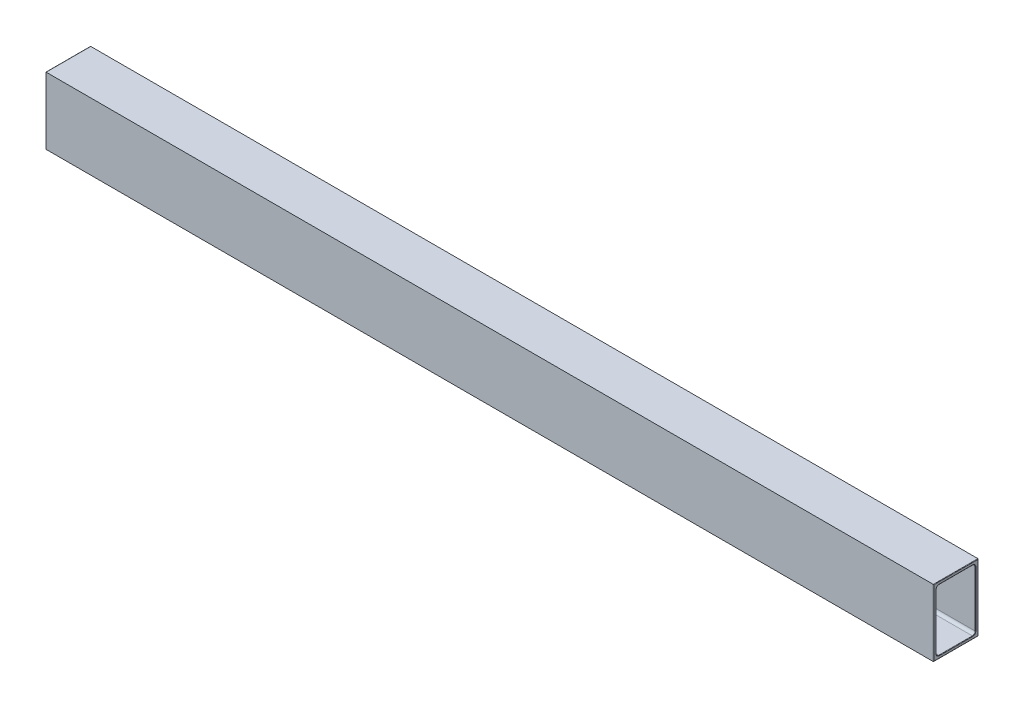
SolidWorks part; units mm, degrees
material "ASTM A500 Grade B Steel"
ref_plane "Front Plane" through (0, 0, 0) normal (0, 0, 1) x (1, 0, 0)
ref_plane "Top Plane" through (0, 0, 0) normal (0, 1, 0) x (1, 0, 0)
ref_plane "Right Plane" through (0, 0, 0) normal (1, 0, 0) x (0, 0, -1)
sketch "Sketch1" plane through (0, 0, 0) normal (1, 0, 0) x (0, 0, -1)
  line L0 (-95.25, 12.7) -> (-95.25, 139.7)
  line L1 (0, 0) -> (-101.6, 0)
  line L2 (0, 0) -> (0, 152.4)
  line L3 (0, 152.4) -> (-101.6, 152.4)
  line L4 (-101.6, 0) -> (-101.6, 152.4)
  line L5 (-12.7, 146.05) -> (-88.9, 146.05)
  line L6 (-6.35, 12.7) -> (-6.35, 139.7)
  line L7 (-12.7, 6.35) -> (-88.9, 6.35)
  line L8 (-95.25, 6.35) -> (-95.25, 146.05) construction
  line L9 (-6.35, 6.35) -> (-95.25, 6.35) construction
  line L10 (-6.35, 6.35) -> (-6.35, 146.05) construction
  line L11 (-6.35, 146.05) -> (-95.25, 146.05) construction
  arc A0 (-95.25, 12.7) -> (-88.9, 6.35) centre (-88.9, 12.7) ccw
  arc A1 (-6.35, 12.7) -> (-12.7, 6.35) centre (-12.7, 12.7) cw
  arc A2 (-12.7, 146.05) -> (-6.35, 139.7) centre (-12.7, 139.7) cw
  arc A3 (-95.25, 139.7) -> (-88.9, 146.05) centre (-88.9, 139.7) cw
  dimension "D4" = 6.35
  dimension "D1" = 152.4
  dimension "D2" = 101.6
  dimension "D3" = 6.35
extrude "Boss-Extrude1" add sketch "Sketch1" along normal blind 2022.6236
fillet "Fillet1" radius 1 24 edges at (0, 152.4, 50.8) (2022.6236, 8.2099, 8.2099) (2022.6236, 76.2, 6.35) (2022.6236, 144.1901, 8.2099) (2022.6236, 146.05, 50.8) (2022.6236, 144.1901, 93.3901) (2022.6236, 76.2, 95.25) (2022.6236, 8.2099, 93.3901) (2022.6236, 6.35, 50.8) (2022.6236, 0, 50.8) (2022.6236, 76.2, 101.6) (2022.6236, 152.4, 50.8) (2022.6236, 76.2, 0) (0, 76.2, 95.25) (0, 144.1901, 93.3901) (0, 146.05, 50.8) (0, 144.1901, 8.2099) (0, 76.2, 6.35) (0, 8.2099, 8.2099) (0, 6.35, 50.8) (0, 8.2099, 93.3901) (0, 76.2, 101.6) (0, 0, 50.8) (0, 76.2, 0)
sketch "Sketch2" plane through (0, 0, 0) normal (0, -1, 0) x (1, 0, 0)
  line L0 (2021.6236, 101.6) -> (1, 101.6) construction
  line L1 (858.9118, 101.6) -> (1163.7118, 101.6)
  line L2 (858.9118, 101.6) -> (858.9118, 0)
  line L3 (858.9118, 0) -> (1163.7118, 0)
  line L4 (1163.7118, 101.6) -> (1163.7118, 0)
  line L5 (2021.6236, 0) -> (1, 0) construction
  point P8 (1011.3118, 101.6)
  point P9 (1011.3118, 101.6)
  dimension "D1" = 304.8
split line "Split Line1"
equation "\"D4@Sketch1\"=\"D3@Sketch1\""
